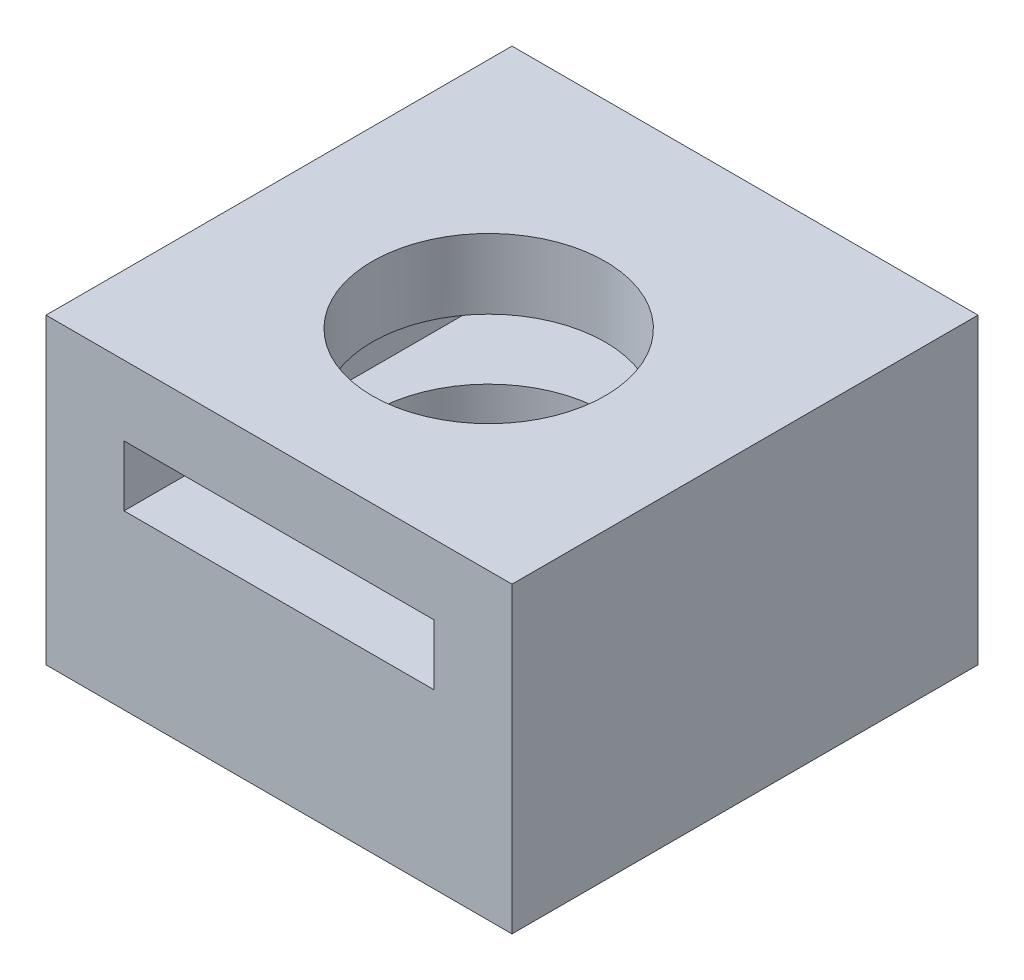
SolidWorks part; units mm, degrees
ref_plane "Alzado" through (0, 0, 0) normal (0, 0, 1) x (1, 0, 0)
ref_plane "Planta" through (0, 0, 0) normal (0, 1, 0) x (1, 0, 0)
ref_plane "Vista lateral" through (0, 0, 0) normal (1, 0, 0) x (0, 0, -1)
sketch "Croquis1" plane through (0, 0, 0) normal (0, 1, 0) x (1, 0, 0)
  line L1 (0, 0) -> (-20, 0)
  line L2 (0, 0) -> (0, -20)
  line L3 (0, -20) -> (-20, -20)
  line L4 (-20, 0) -> (-20, -20)
  dimension "D1" = 20
  dimension "D2" = 20
extrude "Saliente-Extruir1" add sketch "Croquis1" along normal blind 13
sketch "Croquis3" plane through (0, 0, 20) normal (0, 0, 1) x (1, 0, 0)
  line L0 (-16.65, 8.7) -> (-20, 8.7) construction
  line L1 (-16.65, 10) -> (-3.35, 10)
  line L2 (-16.65, 10) -> (-16.65, 7.4)
  line L3 (-16.65, 7.4) -> (-3.35, 7.4)
  line L4 (-3.35, 10) -> (-3.35, 7.4)
  line L5 (-20, 13) -> (-20, 0) construction
  line L6 (-3.35, 8.7) -> (0, 8.7) construction
  line L7 (0, 13) -> (0, 0) construction
  line L8 (-10, 10) -> (-10, 13) construction
  line L9 (-20, 13) -> (0, 13) construction
  dimension "D1" = 2.6
  dimension "D2" = 13.3
  dimension "D3" = 3.35
  dimension "D4" = 3
extrude "Cortar-Extruir1" cut sketch "Croquis3" against normal blind 18
sketch "Croquis4" plane through (0, 13, 0) normal (0, 1, 0) x (1, 0, 0)
  line L0 (-10, -11) -> (-10, 0) construction
  line L1 (0, 0) -> (-20, 0) construction
  line L2 (-10, -11) -> (0, -11) construction
  line L3 (0, -20) -> (0, 0) construction
  circle A0 centre (-10, -11) radius 5
extrude "Cortar-Extruir2" cut sketch "Croquis4" against normal up to surface (13 mm away) up to face at (-10, 0, 10)
